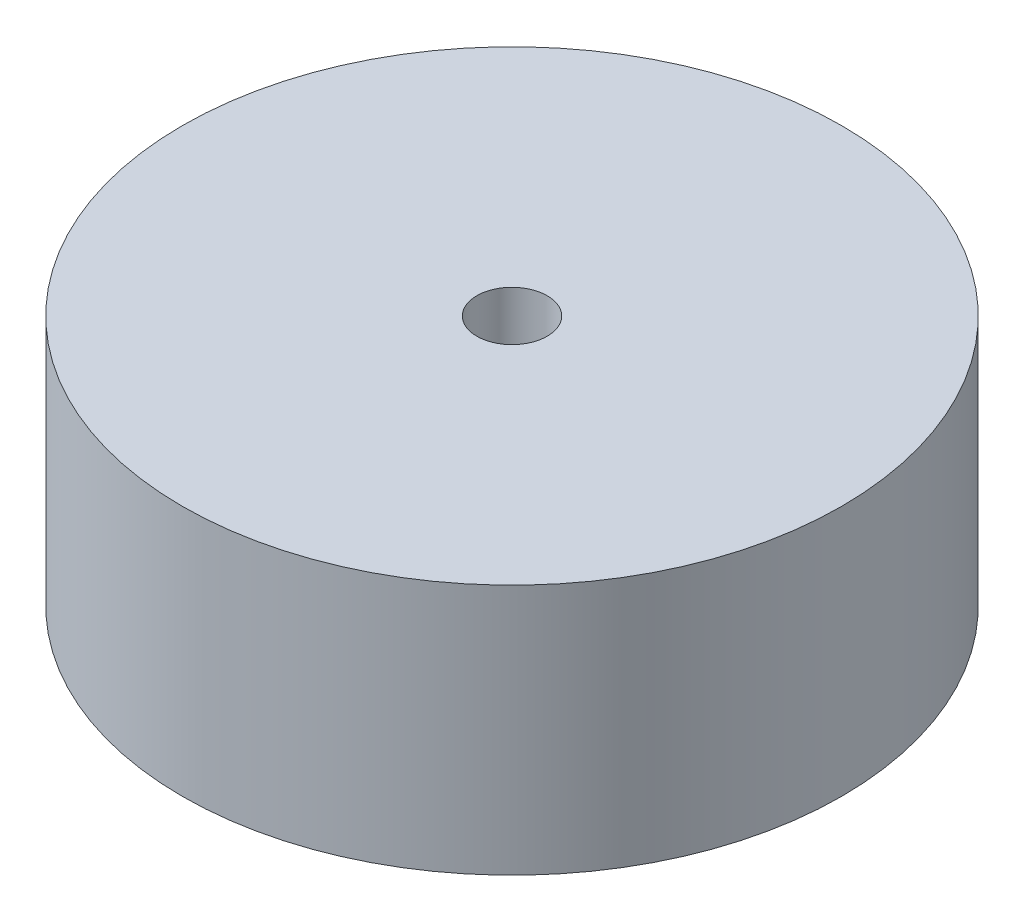
SolidWorks part; units mm, degrees
material "Balsa"
ref_plane "Front Plane" through (0, 0, 0) normal (0, 0, 1) x (1, 0, 0)
ref_plane "Top Plane" through (0, 0, 0) normal (0, 1, 0) x (1, 0, 0)
ref_plane "Right Plane" through (0, 0, 0) normal (1, 0, 0) x (0, 0, -1)
sketch "Sketch1" plane through (0, 0, 0) normal (0, 1, 0) x (1, 0, 0)
  circle A0 centre (0, 0) radius 33.3375
  dimension "D1" = 66.675
extrude "Boss-Extrude1" add sketch "Sketch1" along normal blind 25.4
sketch "Sketch2" plane through (0, 25.4, 0) normal (0, 1, 0) x (1, 0, 0)
  circle A0 centre (0, 0) radius 3.556
  dimension "D1" = 7.112
extrude "Cut-Extrude1" cut sketch "Sketch2" against normal blind 6.35
